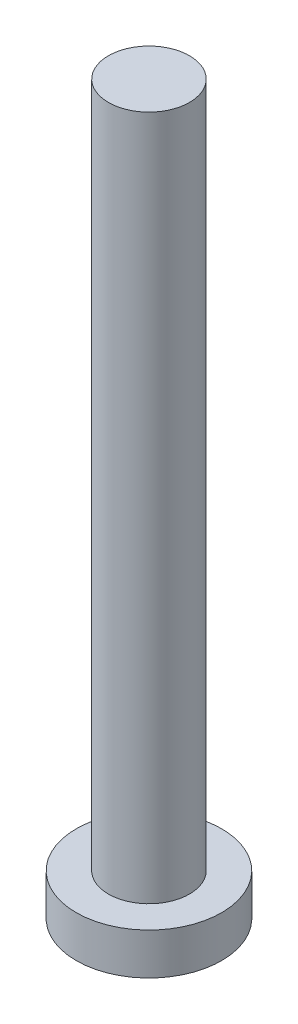
SolidWorks part; units mm, degrees
material "Plain Carbon Steel"
ref_plane "Front Plane" through (0, 0, 0) normal (0, 0, 1) x (1, 0, 0)
ref_plane "Top Plane" through (0, 0, 0) normal (0, 1, 0) x (1, 0, 0)
ref_plane "Right Plane" through (0, 0, 0) normal (1, 0, 0) x (0, 0, -1)
sketch "Sketch1" plane through (0, 0, 0) normal (0, 1, 0) x (1, 0, 0)
  circle A0 centre (0, 0) radius 7
  dimension "D1" = 14
extrude "Boss-Extrude1" add sketch "Sketch1" along normal blind 4 from offset 4
sketch "Sketch2" plane through (0, 0, 0) normal (0, 1, 0) x (1, 0, 0)
  circle A0 centre (0, 0) radius 3.9
  dimension "D1" = 7.8
extrude "Boss-Extrude2" add sketch "Sketch2" along normal blind 66 from offset 0
